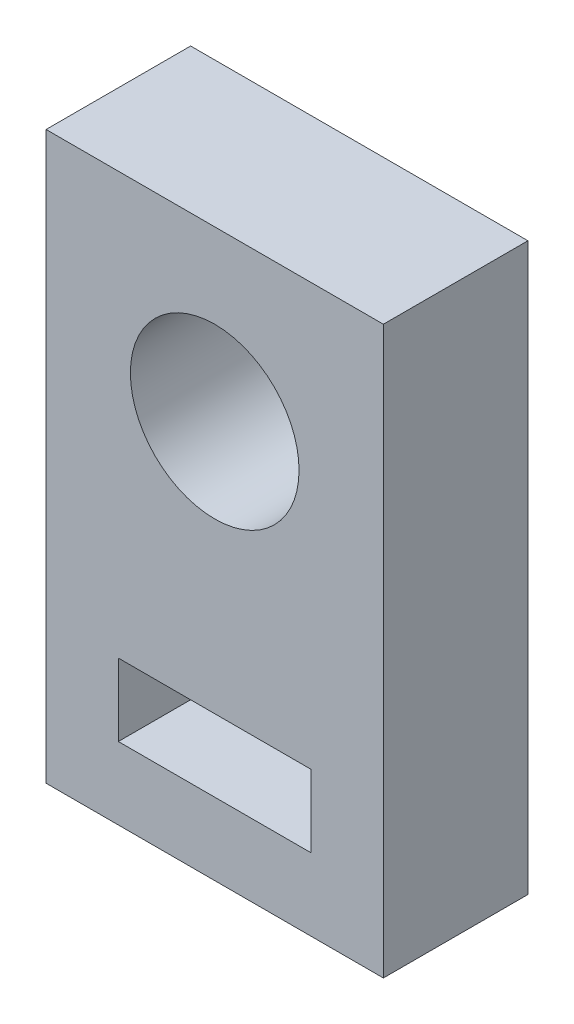
SolidWorks part; units mm, degrees
ref_plane "Front Plane" through (0, 0, 0) normal (0, 0, 1) x (1, 0, 0)
ref_plane "Top Plane" through (0, 0, 0) normal (0, 1, 0) x (1, 0, 0)
ref_plane "Right Plane" through (0, 0, 0) normal (1, 0, 0) x (0, 0, -1)
sketch "Sketch1" plane through (0, 0, 0) normal (0, 0, 1) x (1, 0, 0)
  line L0 (0.1519, 5.0356) -> (0.1519, -1.9644) construction
  line L1 (-6.8481, -7.9644) -> (7.1519, -7.9644)
  line L2 (-6.8481, -7.9644) -> (-6.8481, 15.5356)
  line L3 (-6.8481, 15.5356) -> (7.1519, 15.5356)
  line L4 (7.1519, -7.9644) -> (7.1519, 15.5356)
  line L6 (-6.8481, 15.5356) -> (7.1519, 15.5356)
  line L7 (-3.8481, -4.9644) -> (4.1519, -4.9644)
  line L8 (-3.8481, -4.9644) -> (-3.8481, -1.9644)
  line L9 (-3.8481, -1.9644) -> (4.1519, -1.9644)
  line L10 (4.1519, -4.9644) -> (4.1519, -1.9644)
  line L11 (-3.8481, -4.9644) -> (4.1519, -1.9644) construction
  line L12 (-3.8481, -1.9644) -> (4.1519, -4.9644) construction
  line L13 (-6.8481, 15.5356) -> (-6.8481, -7.9644)
  line L14 (-6.8481, -7.9644) -> (7.1519, -7.9644)
  line L15 (7.1519, 15.5356) -> (7.1519, -7.9644)
  line L16 (-3.8481, -1.9644) -> (4.1519, -1.9644)
  line L17 (-3.8481, -1.9644) -> (-3.8481, -4.9644)
  line L18 (-3.8481, -4.9644) -> (4.1519, -4.9644)
  line L19 (4.1519, -1.9644) -> (4.1519, -4.9644)
  circle A0 centre (0.1519, 8.5356) radius 3.5
  circle A1 centre (0.1519, 8.5356) radius 3.5
  point P0 (0.1519, 3.7856)
  point P8 (0.1519, -3.4644)
  dimension "D1" = 7
  dimension "D2" = 8
  dimension "D3" = 3
  dimension "D4" = 3
  dimension "D5" = 7
  dimension "D6" = 7
  dimension "D7" = 3
  dimension "D8" = 14
  dimension "D9" = 23.5
extrude "Boss-Extrude2" add sketch "Sketch1" along normal blind 6 contours L1 L4 L3 L2 A0 L10 L7 L8 L9
